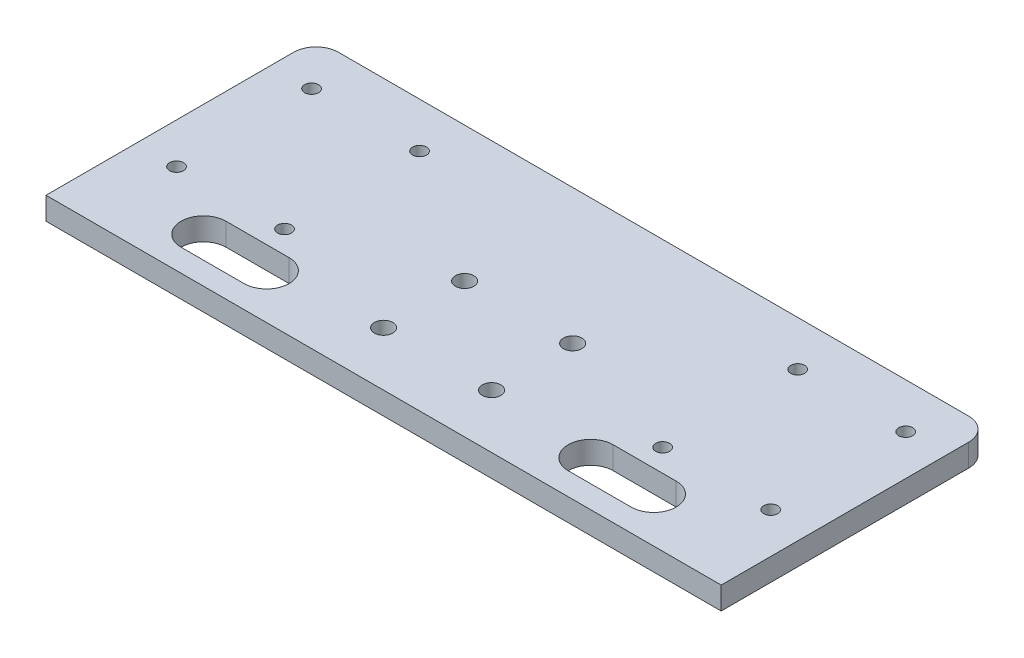
SolidWorks part; units mm, degrees
material "Thornel Mat VMA"
ref_plane "前视基准面" through (0, 0, 0) normal (0, 0, 1) x (1, 0, 0)
ref_plane "上视基准面" through (0, 0, 0) normal (0, 1, 0) x (1, 0, 0)
ref_plane "右视基准面" through (0, 0, 0) normal (1, 0, 0) x (0, 0, -1)
sketch "草图1" plane through (0, 0, 0) normal (0, 1, 0) x (1, 0, 0)
  line L1 (-75, 30) -> (75, 30)
  line L2 (-75, 30) -> (-75, -30)
  line L3 (-75, -30) -> (75, -30)
  line L4 (75, 30) -> (75, -30)
  line L5 (-75, 30) -> (75, -30) construction
  line L6 (-75, -30) -> (75, 30) construction
  point P0 (0, 0)
  dimension "D1" = 150
  dimension "D2" = 60
extrude "凸台-拉伸1" add sketch "草图1" along normal blind 5
ref_plane "基准面1" through (0, 0, 0) normal (0, -1, 0) x (-1, 0, 0)
sketch "草图2" plane through (0, 0, 0) normal (0, -1, 0) x (-1, 0, 0)
  circle A0 centre (-66, 20) radius 1.55
  circle A1 centre (-42, 20) radius 1.55
  circle A2 centre (-66, -10) radius 1.55
  circle A3 centre (-42, -10) radius 1.55
  circle A4 centre (42, 20) radius 1.55
  circle A5 centre (66, 20) radius 1.55
  circle A6 centre (42, -10) radius 1.55
  circle A7 centre (66, -10) radius 1.55
extrude "切除-拉伸1" cut sketch "草图2" against normal blind 10
ref_plane "基准面2" through (0, 5, 0) normal (0, 1, 0) x (1, 0, 0)
sketch "草图3" plane through (0, 5, 0) normal (0, 1, 0) x (1, 0, 0)
  circle A0 centre (-12, 0) radius 2.05
  circle A1 centre (12, 0) radius 2.05
  circle A2 centre (-12, -18) radius 2.05
  circle A3 centre (12, -18) radius 2.05
extrude "切除-拉伸2" cut sketch "草图3" against normal through all
fillet "圆角1" radius 5 2 edges at (-75, 2.5, -30) (75, 2.5, -30)
sketch "草图4" plane through (0, 5, 0) normal (0, 1, 0) x (1, 0, 0)
  line L0 (-50, -20) -> (-36, -20) construction
  line L1 (-50, -15) -> (-36, -15)
  line L2 (-50, -25) -> (-36, -25)
  line L3 (-75, -30) -> (75, -30) construction
  line L4 (-75, 25) -> (-75, -30) construction
  line L5 (0, 30) -> (0, -30) construction
  line L6 (70, 30) -> (-70, 30) construction
  line L7 (50, -20) -> (36, -20) construction
  line L8 (50, -15) -> (36, -15)
  line L9 (50, -25) -> (36, -25)
  arc A0 (-50, -15) -> (-50, -25) centre (-50, -20) ccw
  arc A1 (-36, -25) -> (-36, -15) centre (-36, -20) ccw
  arc A2 (50, -15) -> (50, -25) centre (50, -20) cw
  arc A3 (36, -25) -> (36, -15) centre (36, -20) cw
  point P2 (-43, -20)
  point P17 (43, -20)
  dimension "D2" = 5
  dimension "D4" = 25
  dimension "D1" = 14
  dimension "D3" = 5
extrude "切除-拉伸3" cut sketch "草图4" against normal blind 10
